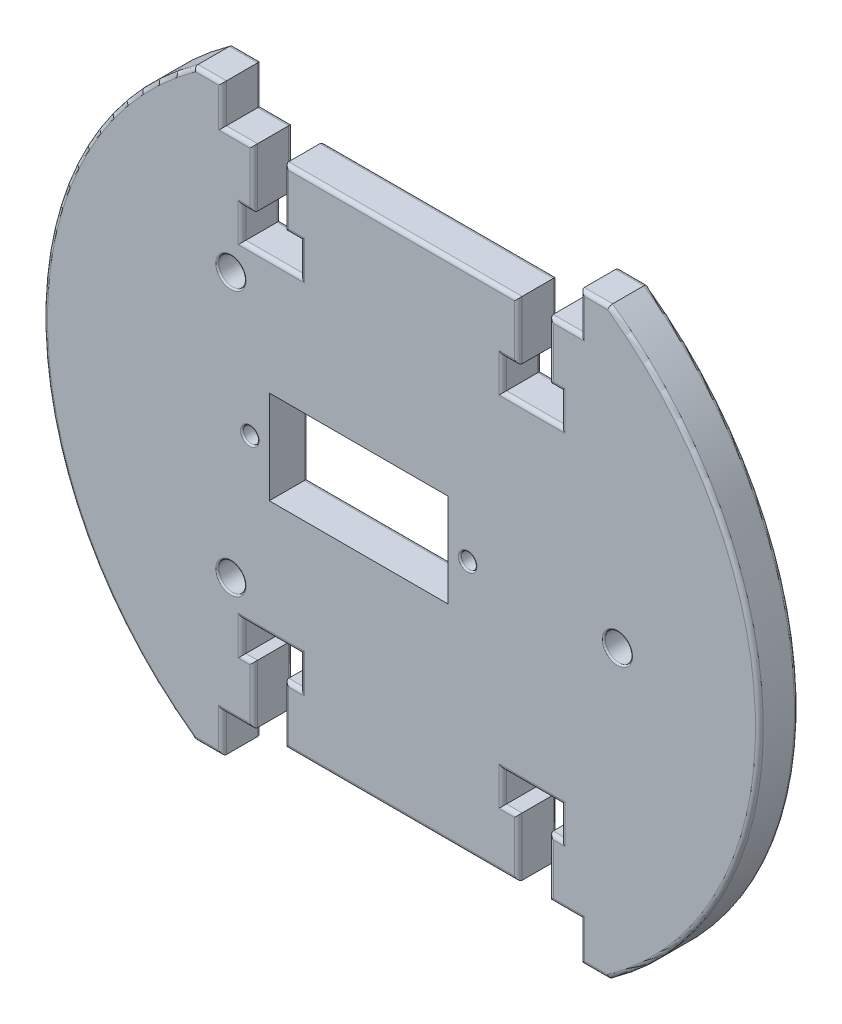
SolidWorks part; units mm, degrees
ref_plane "Front Plane" through (0, 0, 0) normal (0, 0, 1) x (1, 0, 0)
ref_plane "Top Plane" through (0, 0, 0) normal (0, 1, 0) x (1, 0, 0)
ref_plane "Right Plane" through (0, 0, 0) normal (1, 0, 0) x (0, 0, -1)
sketch "Sketch1" plane through (0, 0, 0) normal (0, 0, 1) x (1, 0, 0)
  line L0 (0, 0) -> (0, 47606.8805) construction
  line L1 (0, 0) -> (-47606.8805, 0) construction
  line L2 (26.6411, 37.5) -> (23, 37.5)
  line L3 (-23, 37.5) -> (-26.6411, 37.5)
  line L5 (-23, 37.5) -> (-23, 32.5)
  line L6 (-23, 32.5) -> (23, 32.5)
  line L7 (23, 37.5) -> (23, 32.5)
  line L8 (23, -37.5) -> (23, -32.5)
  line L9 (-23, -32.5) -> (23, -32.5)
  line L10 (-23, -37.5) -> (-23, -32.5)
  line L11 (-23, -37.5) -> (-26.6411, -37.5)
  line L12 (26.6411, -37.5) -> (23, -37.5)
  line L14 (-17, 6) -> (6, 6)
  line L15 (-17, 6) -> (-17, -6)
  line L16 (-17, -6) -> (6, -6)
  line L17 (6, 6) -> (6, -6)
  line L18 (-17, 6) -> (6, -6) construction
  line L19 (-17, -6) -> (6, 6) construction
  arc A0 (-26.6411, 37.5) -> (-26.6411, -37.5) centre (0, 0) ccw
  arc A1 (26.6411, -37.5) -> (26.6411, 37.5) centre (0, 0) ccw
  circle A2 centre (8.5, 0) radius 1
  circle A3 centre (-19.5, 0) radius 1
  circle A4 centre (-21.93, -17) radius 1.75
  circle A5 centre (-21.93, 17) radius 1.75
  circle A6 centre (27.75, 0) radius 1.75
  point P18 (-5.5, 0)
  dimension "D1" = 92
  dimension "D8" = 2
  dimension "D11" = 34
  dimension "D14" = 3.5
  dimension "D2" = 37.5
  dimension "D3" = 46
  dimension "D4" = 5
  dimension "D5" = 6
  dimension "D6" = 23
  dimension "D7" = 12
  dimension "D9" = 2.5
  dimension "D10" = 2.5
  dimension "D12" = 21.93
  dimension "D13" = 27.75
  dimension "D15" = 27.7475
extrude "Boss-Extrude1" add sketch "Sketch1" along normal blind 5
sketch "Sketch3" plane through (0, 0, 0) normal (0, 0, -1) x (-1, 0, 0)
  line L0 (0, 0) -> (0, 50000) construction
  line L1 (19, 32.5) -> (15, 32.5)
  line L2 (0, 0) -> (-50000, 0) construction
  line L3 (-23, 32.5) -> (23, 32.5) construction
  line L4 (-19, 32.5) -> (-15, 32.5)
  line L5 (-19, 32.5) -> (-19, 25)
  line L6 (-19, 25) -> (-15, 25)
  line L7 (-15, 32.5) -> (-15, 25)
  line L8 (-23, 37.5) -> (-23, 32.5) construction
  line L9 (-20.5, 25) -> (-13, 25)
  line L10 (-20.5, 25) -> (-20.5, 21)
  line L11 (-20.5, 21) -> (-13, 21)
  line L12 (-13, 25) -> (-13, 21)
  line L13 (20.5, 25) -> (13, 25)
  line L14 (20.5, 25) -> (20.5, 21)
  line L15 (19, 32.5) -> (19, 25)
  line L16 (19, 25) -> (15, 25)
  line L17 (13, 25) -> (13, 21)
  line L18 (15, 32.5) -> (15, 25)
  line L19 (20.5, 21) -> (13, 21)
  line L20 (20.5, -21) -> (13, -21)
  line L21 (15, -32.5) -> (15, -25)
  line L22 (13, -25) -> (13, -21)
  line L23 (19, -25) -> (15, -25)
  line L24 (19, -32.5) -> (19, -25)
  line L25 (20.5, -25) -> (20.5, -21)
  line L26 (20.5, -25) -> (13, -25)
  line L27 (-13, -25) -> (-13, -21)
  line L28 (-20.5, -21) -> (-13, -21)
  line L29 (-20.5, -25) -> (-20.5, -21)
  line L30 (-20.5, -25) -> (-13, -25)
  line L31 (-15, -32.5) -> (-15, -25)
  line L32 (-19, -25) -> (-15, -25)
  line L33 (-19, -32.5) -> (-19, -25)
  line L34 (-19, -32.5) -> (-15, -32.5)
  line L35 (19, -32.5) -> (15, -32.5)
  line M11 (-23, -32.5) -> (23, -32.5)
  line M17 (23, 32.5) -> (-23, 32.5)
  dimension "D1" = 4
  dimension "D2" = 4
  dimension "D3" = 7.5
  dimension "D4" = 4
  dimension "D5" = 7.5
  dimension "D6" = 1.5
extrude "Cut-Extrude1" cut sketch "Sketch3" against normal blind 5 contours L18 L13 L15 M17 | L19 L14 L13 L17 | L7 L5 L6 M17 | L12 L9 L6 L10 L11 | L29 L30 L27 L28 | L33 L31 L30 M11 | L24 L23 L21 M11 | L26 L25 L20 L22 L23
fillet "Fillet1" radius 0.5 48 edges at (0, -32.5, 0) (15, -28.75, 0) (19.75, -25, 0) (13, -23, 0) (16.75, -21, 0) (20.5, -23, 0) (14, -25, 0) (19, -28.75, 0) (21, -32.5, 0) (23, -35, 0) (24.8206, -37.5, 0) (46, 0, 0) (24.8206, 37.5, 0) (23, 35, 0) (21, 32.5, 0) (19, 28.75, 0) (14, 25, 0) (20.5, 23, 0) (16.75, 21, 0) (13, 23, 0) (19.75, 25, 0) (15, 28.75, 0) (0, 32.5, 0) (-15, 28.75, 0) (-19.75, 25, 0) (-13, 23, 0) (-16.75, 21, 0) (-20.5, 23, 0) (-14, 25, 0) (-19, 28.75, 0) (-21, 32.5, 0) (-23, 35, 0) (-24.8206, 37.5, 0) (-46, 0, 0) (-24.8206, -37.5, 0) (-23, -35, 0) (-21, -32.5, 0) (-19, -28.75, 0) (-14, -25, 0) (-20.5, -23, 0) (-16.75, -21, 0) (-13, -23, 0) (-19.75, -25, 0) (-15, -28.75, 0) (-5.5, -6, 0) (-17, 0, 0) (-5.5, 6, 0) (6, 0, 0)
fillet "Fillet2" radius 0.5 44 edges at (-13, -23, 5) (-16.75, -21, 5) (-20.5, -23, 5) (-14, -25, 5) (-19, -28.75, 5) (-21, -32.5, 5) (-23, -35, 5) (-24.8206, -37.5, 5) (-46, 0, 5) (-24.8206, 37.5, 5) (-23, 35, 5) (-21, 32.5, 5) (-19, 28.75, 5) (-14, 25, 5) (-20.5, 23, 5) (-16.75, 21, 5) (-13, 23, 5) (-19.75, 25, 5) (-15, 28.75, 5) (0, 32.5, 5) (15, 28.75, 5) (19.75, 25, 5) (13, 23, 5) (16.75, 21, 5) (20.5, 23, 5) (14, 25, 5) (19, 28.75, 5) (21, 32.5, 5) (23, 35, 5) (24.8206, 37.5, 5) (46, 0, 5) (24.8206, -37.5, 5) (23, -35, 5) (21, -32.5, 5) (19, -28.75, 5) (14, -25, 5) (20.5, -23, 5) (16.75, -21, 5) (13, -23, 5) (19.75, -25, 5) (15, -28.75, 5) (0, -32.5, 5) (-15, -28.75, 5) (-19.75, -25, 5)
fillet "Fillet3" radius 0.2 7 edges at (-20.18, 17, 0) (-20.18, 17, 5) (29.5, 0, 0) (29.5, 0, 5) (9.5, 0, 5) (-18.5, 0, 5) (-20.18, -17, 5)
fillet "Fillet4" radius 0.2 3 edges at (9.5, 0, 0) (-18.5, 0, 0) (-20.18, -17, 0)
